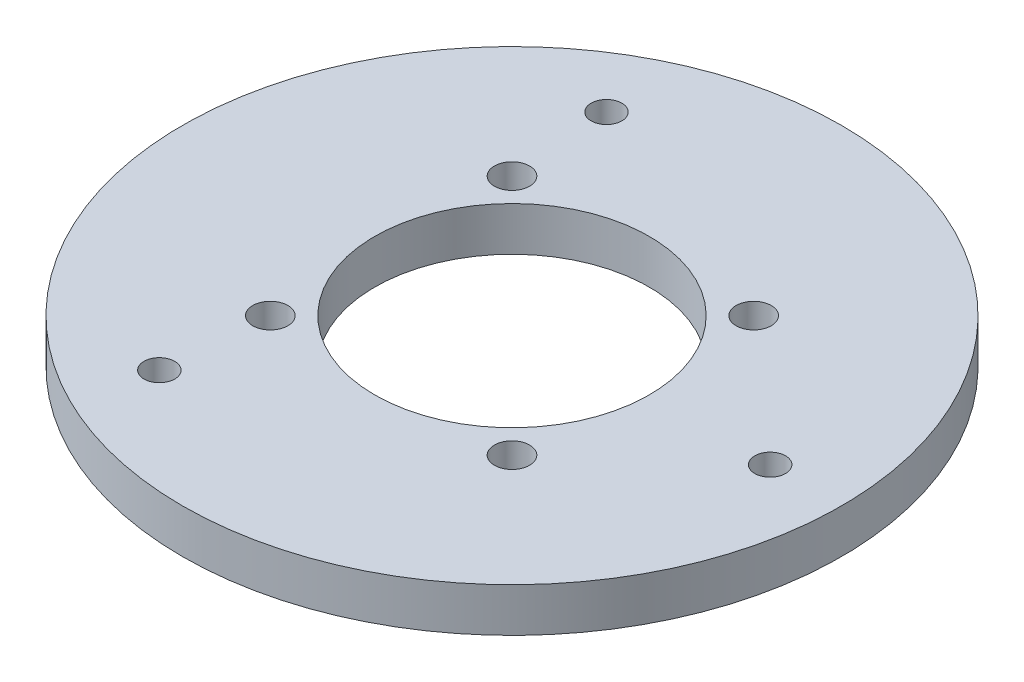
SolidWorks part; units mm, degrees
material "ABS"
ref_plane "前视基准面" through (0, 0, 0) normal (0, 0, 1) x (1, 0, 0)
ref_plane "上视基准面" through (0, 0, 0) normal (0, 1, 0) x (1, 0, 0)
ref_plane "右视基准面" through (0, 0, 0) normal (1, 0, 0) x (0, 0, -1)
sketch "草图1" plane through (0, 0, 0) normal (0, 1, 0) x (1, 0, 0)
  circle A0 centre (0, 0) radius 12.5
  circle A1 centre (0, 0) radius 30
  dimension "D1" = 60
  dimension "D2" = 25
extrude "凸台-拉伸1" add sketch "草图1" along normal blind 4
sketch "草图2" plane through (0, 4, 0) normal (0, 1, 0) x (1, 0, 0)
  line L1 (-11, -11) -> (11, -11) construction
  line L2 (-11, -11) -> (-11, 11) construction
  line L3 (-11, 11) -> (11, 11) construction
  line L4 (11, -11) -> (11, 11) construction
  line L5 (-11, -11) -> (11, 11) construction
  line L6 (-11, 11) -> (11, -11) construction
  circle A0 centre (11, 11) radius 1.6
  circle A1 centre (11, -11) radius 1.6
  circle A2 centre (-11, -11) radius 1.6
  circle A3 centre (-11, 11) radius 1.6
  point P0 (0, 0)
  dimension "D3" = 3.2
  dimension "D1" = 22
  dimension "D2" = 22
extrude "切除-拉伸1" cut sketch "草图2" against normal blind 4
sketch "草图3" plane through (0, 4, 0) normal (0, 1, 0) x (1, 0, 0)
  line L1 (23.5, 0) -> (-11.75, 20.3516) construction
  line L2 (-11.75, 20.3516) -> (-11.75, -20.3516) construction
  line L3 (-11.75, -20.3516) -> (23.5, 0) construction
  circle A0 centre (0, 0) radius 23.5 construction
  circle A1 centre (23.5, 0) radius 1.4
  circle A2 centre (-11.75, 20.3516) radius 1.4
  circle A3 centre (-11.75, -20.3516) radius 1.4
  dimension "D1" = 47
  dimension "D2" = 2.8
extrude "切除-拉伸2" cut sketch "草图3" against normal blind 10
